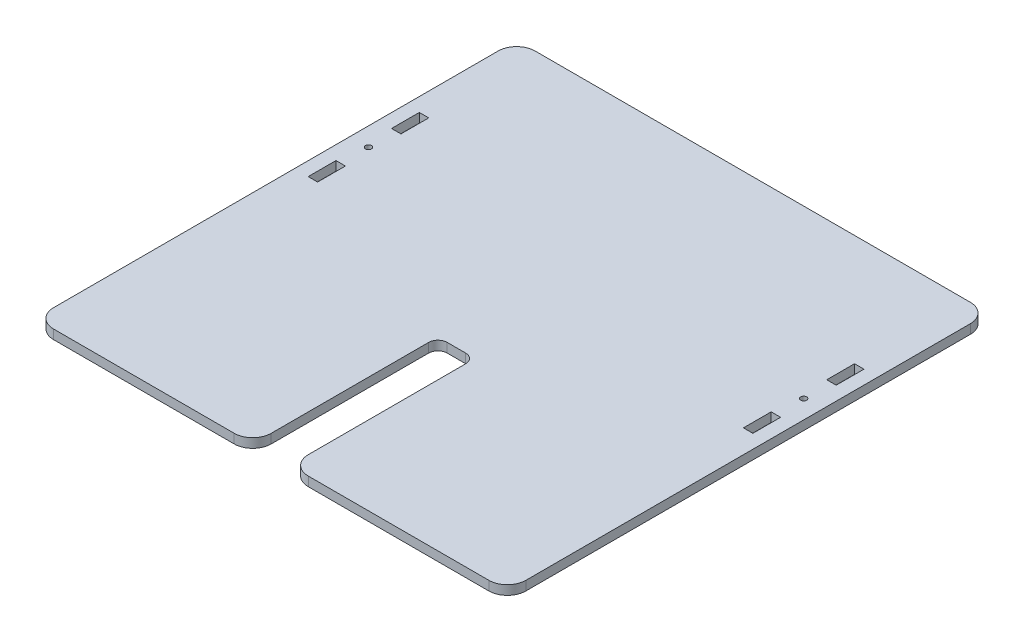
SolidWorks part; units mm, degrees
ref_plane "Front" through (0, 0, 0) normal (0, 0, 1) x (1, 0, 0)
ref_plane "Top" through (0, 0, 0) normal (0, 1, 0) x (1, 0, 0)
ref_plane "Right" through (0, 0, 0) normal (1, 0, 0) x (0, 0, -1)
sketch "Sketch1" plane through (0, 0, 0) normal (0, 1, 0) x (1, 0, 0)
  line L0 (189.7523, 165.2809) -> (189.7523, 150.2809)
  line L1 (-42.6977, 225.2809) -> (192.3023, 225.2809)
  line L2 (-52.6977, 215.2809) -> (-52.6977, -24.7191)
  line L3 (-42.6977, -34.7191) -> (54.8023, -34.7191)
  line L4 (202.3023, 215.2809) -> (202.3023, -24.7191)
  line L5 (189.7523, 150.2809) -> (194.8523, 150.2809)
  line L6 (194.8523, 150.2809) -> (194.8523, 165.2809)
  line L7 (194.8523, 165.2809) -> (189.7523, 165.2809)
  line L8 (192.3023, 150.2809) -> (192.3023, 120.2809) construction
  line L9 (189.7523, 120.2809) -> (189.7523, 105.2809)
  line L10 (189.7523, 105.2809) -> (194.8523, 105.2809)
  line L11 (194.8523, 105.2809) -> (194.8523, 120.2809)
  line L12 (194.8523, 120.2809) -> (189.7523, 120.2809)
  line L13 (202.3023, 135.2809) -> (192.3023, 135.2809) construction
  line L14 (-52.6977, 135.2809) -> (-42.6977, 135.2809) construction
  line L15 (94.8023, -34.7191) -> (192.3023, -34.7191)
  line L16 (-45.2477, 165.2809) -> (-45.2477, 150.2809)
  line L17 (-45.2477, 150.2809) -> (-40.1477, 150.2809)
  line L18 (-40.1477, 150.2809) -> (-40.1477, 165.2809)
  line L19 (-40.1477, 165.2809) -> (-45.2477, 165.2809)
  line L20 (-42.6977, 150.2809) -> (-42.6977, 120.2809) construction
  line L21 (-45.2477, 120.2809) -> (-45.2477, 105.2809)
  line L22 (-45.2477, 105.2809) -> (-40.1477, 105.2809)
  line L23 (-40.1477, 105.2809) -> (-40.1477, 120.2809)
  line L24 (-40.1477, 120.2809) -> (-45.2477, 120.2809)
  line L25 (69.8023, 65.2809) -> (79.8023, 65.2809)
  line L27 (64.8023, 60.2809) -> (64.8023, -24.7191)
  line L28 (84.8023, 60.2809) -> (84.8023, -24.7191)
  arc A0 (-52.6977, -24.7191) -> (-42.6977, -34.7191) centre (-42.6977, -24.7191) ccw
  arc A1 (192.3023, -34.7191) -> (202.3023, -24.7191) centre (192.3023, -24.7191) ccw
  arc A2 (192.3023, 225.2809) -> (202.3023, 215.2809) centre (192.3023, 215.2809) cw
  arc A3 (-42.6977, 225.2809) -> (-52.6977, 215.2809) centre (-42.6977, 215.2809) ccw
  circle A4 centre (192.3023, 135.2809) radius 1.6
  circle A5 centre (-42.6977, 135.2809) radius 1.6
  arc A6 (79.8023, 65.2809) -> (84.8023, 60.2809) centre (79.8023, 60.2809) cw
  arc A7 (69.8023, 65.2809) -> (64.8023, 60.2809) centre (69.8023, 60.2809) ccw
  arc A8 (84.8023, -24.7191) -> (94.8023, -34.7191) centre (94.8023, -24.7191) ccw
  arc A9 (64.8023, -24.7191) -> (54.8023, -34.7191) centre (54.8023, -24.7191) cw
  dimension "D1" = 5
  dimension "D2" = 10
extrude "Boss-Extrude1" add sketch "Sketch1" along normal blind 5
